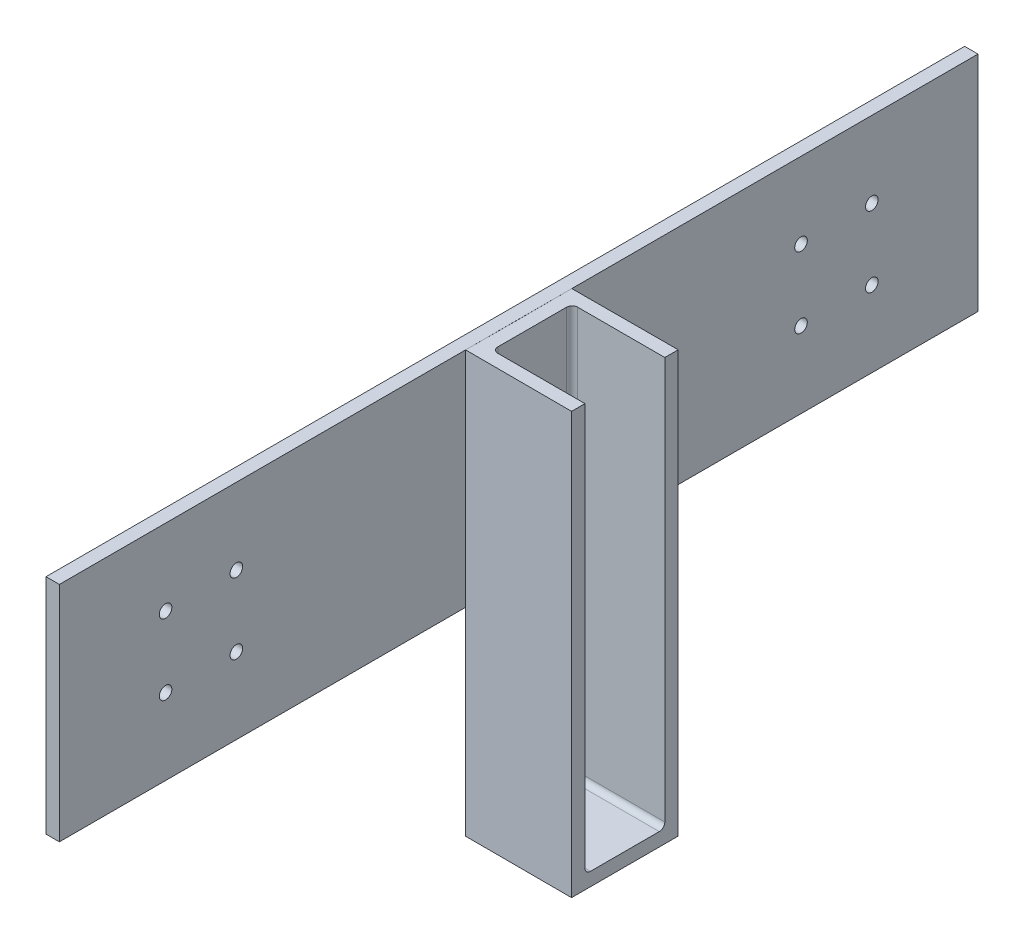
SolidWorks part; units mm, degrees
ref_plane "Front Plane" through (0, 0, 0) normal (0, 0, 1) x (1, 0, 0)
ref_plane "Top Plane" through (0, 0, 0) normal (0, 1, 0) x (1, 0, 0)
ref_plane "Right Plane" through (0, 0, 0) normal (1, 0, 0) x (0, 0, -1)
sketch "Sketch1" plane through (0, 0, 0) normal (1, 0, 0) x (0, 0, -1)
  line L0 (-35.9775, 7.9986) -> (128.8225, 7.9986) construction
  line L1 (-35.9775, 27.9986) -> (128.8225, 27.9986)
  line L2 (-35.9775, 27.9986) -> (-35.9775, -12.0014)
  line L3 (-35.9775, -12.0014) -> (128.8225, -12.0014)
  line L4 (128.8225, 27.9986) -> (128.8225, -12.0014)
  line L5 (46.4225, 27.9986) -> (46.4225, -12.0014) construction
  line L6 (-10.5775, 27.9986) -> (-10.5775, -12.0014) construction
  circle A0 centre (-16.9275, 14.3486) radius 1.13
  circle A1 centre (-4.2275, 14.3486) radius 1.13
  circle A2 centre (-4.2275, 1.6486) radius 1.13
  circle A3 centre (-16.9275, 1.6486) radius 1.13
  circle A4 centre (109.7725, 1.6486) radius 1.13
  circle A5 centre (97.0725, 1.6486) radius 1.13
  circle A6 centre (97.0725, 14.3486) radius 1.13
  circle A7 centre (109.7725, 14.3486) radius 1.13
  dimension "D4" = 2.26
  dimension "D5" = 6.35
  dimension "D1" = 164.8
  dimension "D2" = 40
  dimension "D3" = 25.4
  dimension "D6" = 6.35
extrude "Boss-Extrude1" add sketch "Sketch1" along normal blind 2.4
sketch "Sketch2" plane through (0, 27.9986, 0) normal (0, 1, 0) x (1, 0, 0)
  line L0 (1.2, 128.8225) -> (1.2, -35.9775) construction
  line L1 (2.4, 128.8225) -> (0, 128.8225) construction
  line L2 (2.4, -35.9775) -> (0, -35.9775) construction
  line L3 (0, 46.4225) -> (2.4201, 46.4225) construction
  line L4 (2.4, 55.9475) -> (21.45, 55.9878)
  line L5 (21.45, 55.9878) -> (21.45, 53.5878)
  line L6 (0, 128.8225) -> (0, -35.9775) construction
  line L7 (2.4201, 46.4225) -> (2.4, 55.9475)
  line L8 (2.4, 128.8225) -> (2.4, -35.9775) construction
  line L9 (21.45, 53.5878) -> (4.8201, 53.5878)
  line L10 (4.8201, 53.5878) -> (4.8201, 39.2573)
  line L11 (21.45, 39.2573) -> (4.8201, 39.2573)
  line L12 (2.4201, 46.4225) -> (2.4, 36.8975)
  line L13 (21.45, 36.8573) -> (21.45, 39.2573)
  line L14 (2.4, 36.8975) -> (21.45, 36.8573)
  point P18 (4.8201, 46.4225)
  dimension "D1" = 2.4
  dimension "D2" = 9.525
  dimension "D3" = 19.05
  dimension "D4" = 2.4
extrude "Boss-Extrude2" add sketch "Sketch2" against normal blind 75.56
sketch "Sketch3" plane through (0, -47.5614, 0) normal (0, -1, 0) x (1, 0, 0)
  line L1 (4.8201, -39.2573) -> (21.45, -39.2573)
  line L2 (4.8201, -39.2573) -> (4.8201, -53.5878)
  line L3 (4.8201, -53.5878) -> (21.45, -53.5878)
  line L4 (21.45, -39.2573) -> (21.45, -53.5878)
extrude "Boss-Extrude3" add sketch "Sketch3" against normal blind 2.4
fillet "Fillet1" radius 1 5 edges at (13.1351, -45.1614, -39.2573) (13.1351, -45.1614, -53.5878) (4.8201, -45.1614, -46.4225) (4.8201, -8.5814, -53.5878) (4.8201, -8.5814, -39.2573)
